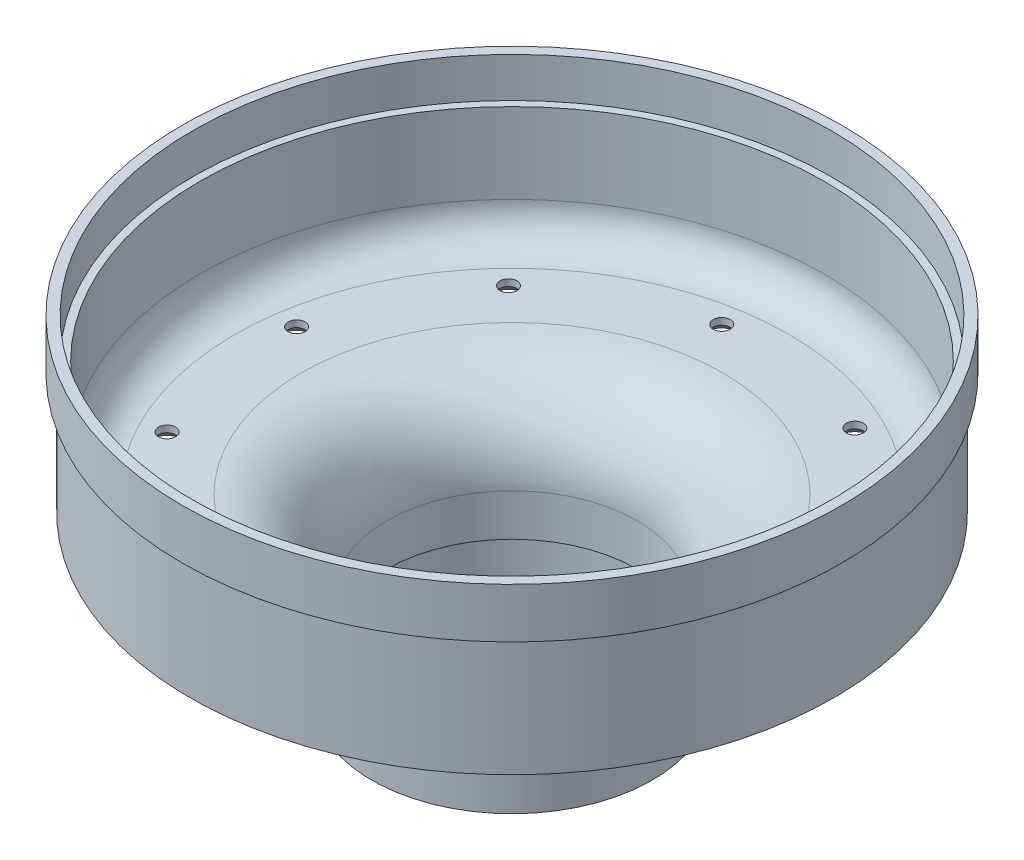
SolidWorks part; units mm, degrees
ref_plane "Ön Düzlem" through (0, 0, 0) normal (0, 0, 1) x (1, 0, 0)
ref_plane "Üst Düzlem" through (0, 0, 0) normal (0, 1, 0) x (1, 0, 0)
ref_plane "Sağ Düzlem" through (0, 0, 0) normal (1, 0, 0) x (0, 0, -1)
sketch "Çizim1" plane through (0, 0, 0) normal (0, 0, 1) x (1, 0, 0)
  line L0 (0, 0) -> (0, 35.704) construction
  line L17 (-26.6, 0.5457) -> (-26.6, 10.5457)
  line L18 (-26.6, 10.5457) -> (-25.1, 10.5457)
  line L19 (-25.1, 10.5457) -> (-25.1, 18.9457)
  line L20 (-42.2, 36.0457) -> (-55.5, 36.0457)
  line L21 (-62.5, 43.0457) -> (-62.5, 59.1293)
  line L22 (-62.5, 59.1293) -> (-64, 59.1293)
  line L23 (-64, 59.1293) -> (-64, 67.1293)
  line L24 (-26.6, 0.5457) -> (-28.1, 0.5457)
  line L25 (-28.1, 0.5457) -> (-28.1, 21.1657)
  line L26 (-39.98, 33.0457) -> (-64.5, 33.0457)
  line L27 (-64.5, 33.0457) -> (-64.5, 57.1293)
  line L28 (-64.5, 57.1293) -> (-66, 57.1293)
  line L29 (-66, 57.1293) -> (-66, 67.1293)
  line L30 (-66, 67.1293) -> (-64, 67.1293)
  arc A0 (-28.1, 21.1657) -> (-39.98, 33.0457) centre (-39.98, 21.1657) ccw
  arc A1 (-25.1, 18.9457) -> (-42.2, 36.0457) centre (-42.2, 18.9457) ccw
  arc A2 (-55.5, 36.0457) -> (-62.5, 43.0457) centre (-55.5, 43.0457) cw
  point P19 (-28.1, 33.0457)
  point P22 (-67.8373, 26.7259)
  point P23 (-25.1, 36.0457)
  point P24 (0, 0)
  point P25 (0, 0)
  point P28 (-64, 61.6807)
  point P29 (-62.5, 36.0457)
  dimension "D8" = 11.88
  dimension "D10" = 17.1
  dimension "D17" = 7
  dimension "D1" = 35.5
  dimension "D2" = 25.5
  dimension "D3" = 1.5
  dimension "D4" = 37.4
  dimension "D5" = 62.5
  dimension "D6" = 25.1
  dimension "D7" = 3
  dimension "D9" = 3
  dimension "D11" = 2
  dimension "D12" = 1.5
  dimension "D13" = 2
  dimension "D14" = 8
  dimension "D15" = 10
  dimension "D16" = 66
revolve "Döndür3" add sketch "Çizim1" angle 360 about L0
sketch "Çizim7" plane through (0, 33.0457, 0) normal (0, -1, 0) x (1, 0, 0)
  point P3 (8.5, 50.5)
  point P6 (20.0057, 52.141)
hole_wizard "M3 Altıgen Alyan Havşa Başlı Kör Vida İçin Havşa4" positions "3B Çizim7" profile "Çizim10" countersink size "M3" standard "ISO" end condition through all
sketch3d "3B Çizim7"
  point P0 (8.5, 33.0457, 50.5)
sketch "Çizim10" plane through (8.5, 33.0457, 50.5) normal (1, 0, 0) x (0, 0, -1)
  line L0 (0, 0) -> (0, 34.0836)
  line L1 (0, 34.0836) -> (1.7, 34.0836)
  line L2 (1.7, 34.0836) -> (1.7, 1.66)
  line L3 (1.7, 1.66) -> (3.36, 0)
  line L5 (3.36, 0) -> (0, 0)
  line L6 (-1.7, 1.66) -> (-3.36, 0) construction
  line L11 (0, -6.35) -> (0, 107.95) construction
  dimension "Thru Hole Dia." = 3.4
  dimension "Thru Hole Depth" = 34.0836
  dimension "Near C'Sink Dia." = 6.72
  dimension "Near C'Sink Angle" = 90
pattern_circular "Dairesel Kaplama2" count 10 over 360 about axis through (0, 0, 0) along (0, 1, 0) of "M3 Altıgen Alyan Havşa Başlı Kör Vida İçin Havşa4"
